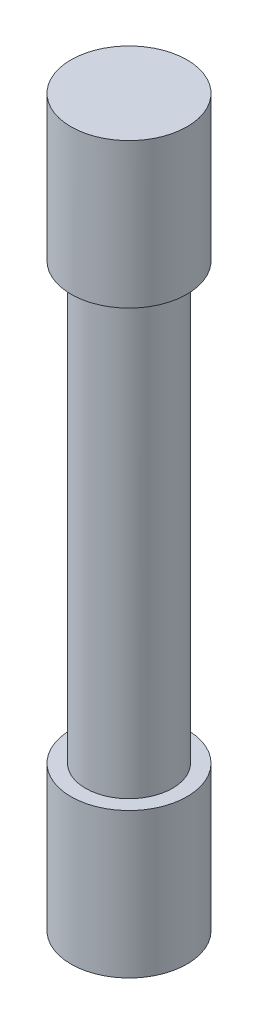
SolidWorks part; units mm, degrees
ref_plane "Front Plane" through (0, 0, 0) normal (0, 0, 1) x (1, 0, 0)
ref_plane "Top Plane" through (0, 0, 0) normal (0, 1, 0) x (1, 0, 0)
ref_plane "Right Plane" through (0, 0, 0) normal (1, 0, 0) x (0, 0, -1)
sketch "Sketch1" plane through (0, 0, 0) normal (0, 1, 0) x (1, 0, 0)
  circle A0 centre (0, 0) radius 4
  dimension "D1" = 8
extrude "Boss-Extrude1" add sketch "Sketch1" along normal blind 50
ref_plane "Plane1" through (0, 25, 0) normal (0, 1, 0) x (1, 0, 0)
sketch "Sketch2" plane through (0, 25, 0) normal (0, 1, 0) x (1, 0, 0)
  circle A0 centre (0, 0) radius 3
  circle A1 centre (0, 0) radius 5.5343
  dimension "D1" = 6
extrude "Cut-Extrude1" cut sketch "Sketch2" against normal blind 15
sketch "Sketch4" plane through (0, 25, 0) normal (0, -1, 0) x (1, 0, 0)
  circle A0 centre (0, 0) radius 3
  circle A1 centre (0, 0) radius 4
  dimension "D1" = 6
extrude "Cut-Extrude2" cut sketch "Sketch4" against normal blind 15
